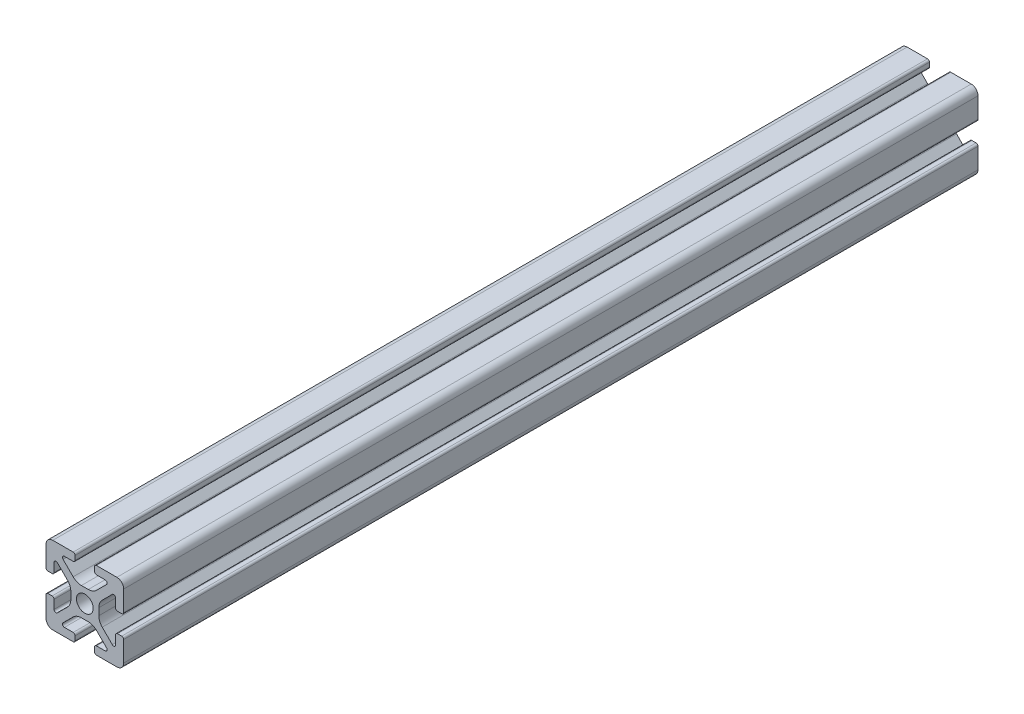
SolidWorks part; units mm, degrees
ref_plane "Front Plane" through (0, 0, 0) normal (0, 0, 1) x (1, 0, 0)
ref_plane "Top Plane" through (0, 0, 0) normal (0, 1, 0) x (1, 0, 0)
ref_plane "Right Plane" through (0, 0, 0) normal (1, 0, 0) x (0, 0, -1)
sketch "Sketch2" plane through (0, 0, 0) normal (0, 0, 1) x (1, 0, 0)
  line L0 (0, 10) -> (0, -10) construction
  line L1 (-10, 0) -> (10, 0) construction
  line L2 (2.5, -10) -> (10, -10)
  line L3 (10, -10) -> (10, -2.5)
  line L4 (2.5, -10) -> (2.5, -7.9246)
  line L5 (2.5, -7.9246) -> (6.4571, -7.9246)
  line L6 (6.4571, -7.9246) -> (2.1325, -3.6)
  line L7 (0, 0) -> (10, -10) construction
  line L8 (10, -2.5) -> (7.9246, -2.5)
  line L9 (7.9246, -2.5) -> (7.9246, -6.4571)
  line L10 (7.9246, -6.4571) -> (3.6, -2.1325)
  line L11 (5.7623, -4.2948) -> (4.2948, -5.7623) construction
  circle A0 centre (0, 0) radius 2.15
  arc A1 (5.25, -7.9246) -> (5.6036, -7.0711) centre (5.25, -7.4246) ccw construction
  point P8 (0, -3.6)
  point P16 (5.0286, -5.0286)
  dimension "Center Hole Diameter" = 4.3
  dimension "D3" = 0.5
  dimension "Rail Height" = 20
  dimension "Rail Width" = 20
  dimension "T-Slot Width" = 5
  dimension "Slot Depth" = 6.4
  dimension "Slot Inner Width" = 11.5
sketch "Sketch3" plane through (0, 0, 0) normal (1, 0, 0) x (0, 0, -1)
  line L0 (-457.2, -10) -> (457.2, -10) construction
  line L1 (-431.8, 0) -> (431.8, 0) construction
  line L2 (0, 10) -> (0, -10) construction
  line L3 (0, 10) -> (0, -10) construction
  point P6 (-431.8, 0)
  point P8 (431.8, 0)
  dimension "Length" = 914.4
  dimension "D1" = 25.4
sketch "Sketch4" plane through (0, 0, 0) normal (0, 0, 1) x (1, 0, 0)
  line L0 (3, -10) -> (8.25, -10)
  line L1 (2.5, -10) -> (10, -10) construction
  line L2 (2.5, -10) -> (2.5, -7.9246) construction
  line L3 (2.5, -7.9246) -> (6.4571, -7.9246) construction
  line L4 (2.5, -8.4246) -> (2.5, -9.5)
  line L5 (3, -7.9246) -> (5.25, -7.9246)
  line L6 (0, -3.6) -> (0.8898, -3.6)
  line L7 (6.4571, -7.9246) -> (2.1325, -3.6) construction
  line L8 (3.0112, -4.4787) -> (5.6036, -7.0711)
  line L9 (10, -10) -> (10, -2.5) construction
  line L10 (7.9246, -6.4571) -> (3.6, -2.1325) construction
  line L11 (7.9246, -2.5) -> (7.9246, -6.4571) construction
  line L12 (7.9246, -5.25) -> (7.9246, -3)
  line L13 (10, -2.5) -> (7.9246, -2.5) construction
  line L14 (8.4246, -2.5) -> (9.5, -2.5)
  line L15 (10, -3) -> (10, -8.25)
  line L16 (7.0711, -5.6036) -> (4.4787, -3.0112)
  line L17 (3.6, 0) -> (3.6, -0.8898)
  line L18 (-10, 0) -> (10, 0) construction
  line L19 (0, -3.6) -> (0, -2.15)
  line L20 (0, 10) -> (0, -10) construction
  line L21 (3.6, 0) -> (2.15, 0)
  arc A0 (2.5, -9.5) -> (3, -10) centre (3, -9.5) ccw
  arc A1 (5.25, -7.9246) -> (5.6036, -7.0711) centre (5.25, -7.4246) ccw construction
  arc A2 (2.5, -8.4246) -> (3, -7.9246) centre (3, -8.4246) cw
  arc A3 (5.25, -7.9246) -> (5.6036, -7.0711) centre (5.25, -7.4246) ccw
  arc A4 (0.8898, -3.6) -> (3.0112, -4.4787) centre (0.8898, -6.6) cw
  arc A5 (8.25, -10) -> (10, -8.25) centre (8.25, -8.25) ccw
  arc A6 (7.0711, -5.6036) -> (7.9246, -5.25) centre (7.4246, -5.25) ccw
  arc A7 (7.9246, -3) -> (8.4246, -2.5) centre (8.4246, -3) cw
  arc A8 (9.5, -2.5) -> (10, -3) centre (9.5, -3) cw
  arc A9 (4.4787, -3.0112) -> (3.6, -0.8898) centre (6.6, -0.8898) cw
  circle A10 centre (0, 0) radius 2.15 construction
  arc A11 (0, -2.15) -> (2.15, 0) centre (0, 0) ccw
  dimension "D1" = 1.75
  dimension "D2" = 3
extrude "Boss-Extrude1" add sketch "Sketch4" along normal mid plane 220
mirror "Mirror1" about plane through (0, 0, 0) normal (1, 0, 0) of bodies 134
mirror "Mirror2" about plane through (0, 0, 0) normal (0, 1, 0) of bodies 135
equation "\"D3@Sketch2\"=\"T-Slot Width@Sketch2\"*0.1"
equation "\"D1@Sketch4\"=\"D3@Sketch2\"*3.5"
equation "\"D2@Sketch4\"=\"D3@Sketch2\"*6"
equation "\"D1@Boss-Extrude1\"=\"Length@Sketch3\""
